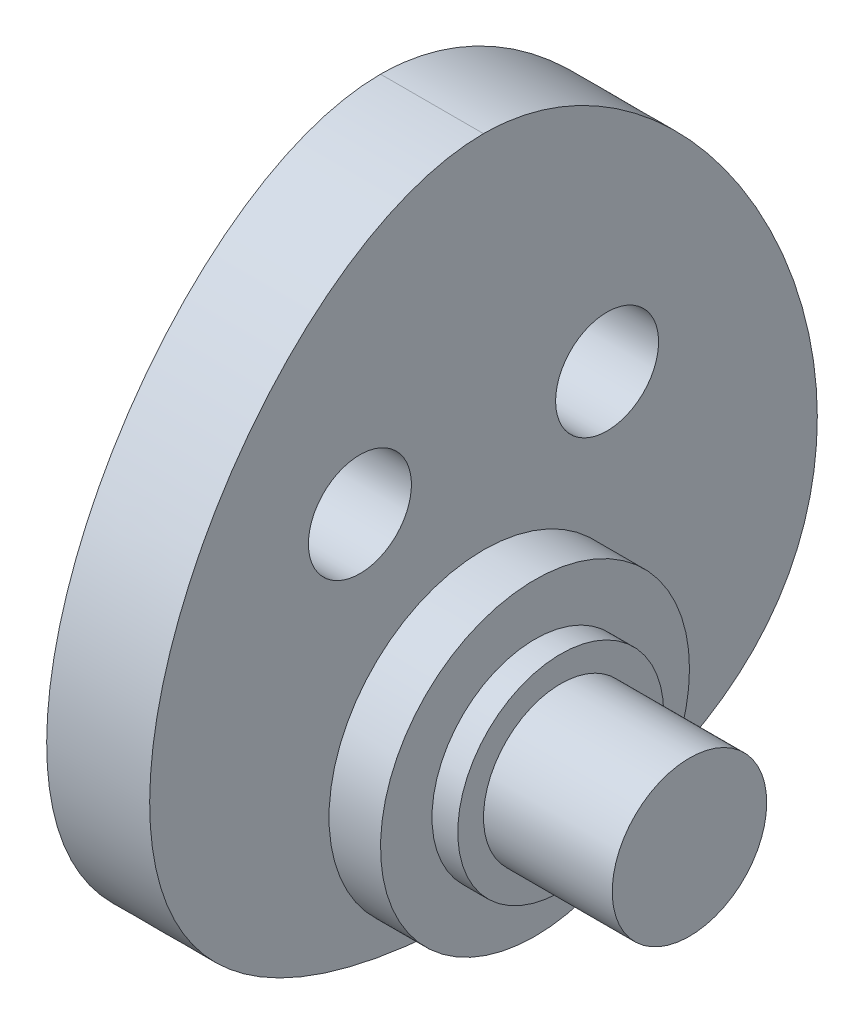
SolidWorks part; units mm, degrees
ref_plane "Front Plane" through (0, 0, 0) normal (0, 0, 1) x (1, 0, 0)
ref_plane "Top Plane" through (0, 0, 0) normal (0, 1, 0) x (1, 0, 0)
ref_plane "Right Plane" through (0, 0, 0) normal (1, 0, 0) x (0, 0, -1)
sketch "Sketch1" plane through (0, 0, 0) normal (1, 0, 0) x (0, 0, -1)
  line L0 (0, 0) -> (0, -3) construction
  line L1 (0, 0) -> (-2, -3.4641) construction
  line L2 (0, 0) -> (-4.3301, -2.5) construction
  line L3 (0, 0) -> (-6, 0) construction
  line L4 (0, 0) -> (-6.0622, 3.5) construction
  line L5 (0, 0) -> (-4, 6.9282) construction
  line L6 (0, 0) -> (0, 10) construction
  circle A4 centre (0, 0) radius 2.5
  spline S0 degree 3 poles (0, 10) (-5.5754, 10) (-11.2568, -3) (0, -3) knots 0 0 0 0 1 1 1 1
  spline S1 degree 3 poles (0, 10) (5.5754, 10) (11.2568, -3) (0, -3) knots 0 0 0 0 1 1 1 1
  dimension "D2" = 10
  dimension "D4" = 5
  dimension "D5" = 3
  dimension "D6" = 4
  dimension "D7" = 5
  dimension "D8" = 6
  dimension "D9" = 7
  dimension "D10" = 8
  dimension "D11" = 30
  dimension "D12" = 30
  dimension "D13" = 30
  dimension "D14" = 30
  dimension "D15" = 30
extrude "Boss-Extrude1" add sketch "Sketch1" along normal blind 2
sketch "Sketch2" plane through (2, 0, 0) normal (1, 0, 0) x (0, 0, -1)
  circle A0 centre (0, 0) radius 3
  dimension "D2" = 6
extrude "Boss-Extrude2" add sketch "Sketch2" along normal blind 4
sketch "Sketch3" plane through (0, 0, 0) normal (-1, 0, 0) x (0, 0, 1)
  circle A1 centre (-2.4, 4.8) radius 1
  circle A2 centre (2.4, 4.8) radius 1
  dimension "D2" = 2
  dimension "D3" = 4.8
  dimension "D5" = 2.4
  dimension "D6" = 2.4
extrude "Cut-Extrude1" cut sketch "Sketch3" against normal up to next
chamfer "Chamfer1" distance 1 angle 45 1 edges at (2, 0, -2.5)
sketch "Sketch4" plane through (6, 0, 0) normal (1, 0, 0) x (0, 0, -1)
  circle A0 centre (0, 0) radius 1.5
  dimension "D1" = 3
extrude "Cut-Extrude2" cut sketch "Sketch4" against normal blind 2.5 flip side to cut
sketch "Sketch5" plane through (3.5, 0, 0) normal (1, 0, 0) x (0, 0, -1)
  circle A0 centre (0, 0) radius 2
  dimension "D1" = 4
extrude "Cut-Extrude3" cut sketch "Sketch5" against normal blind 0.5 flip side to cut
